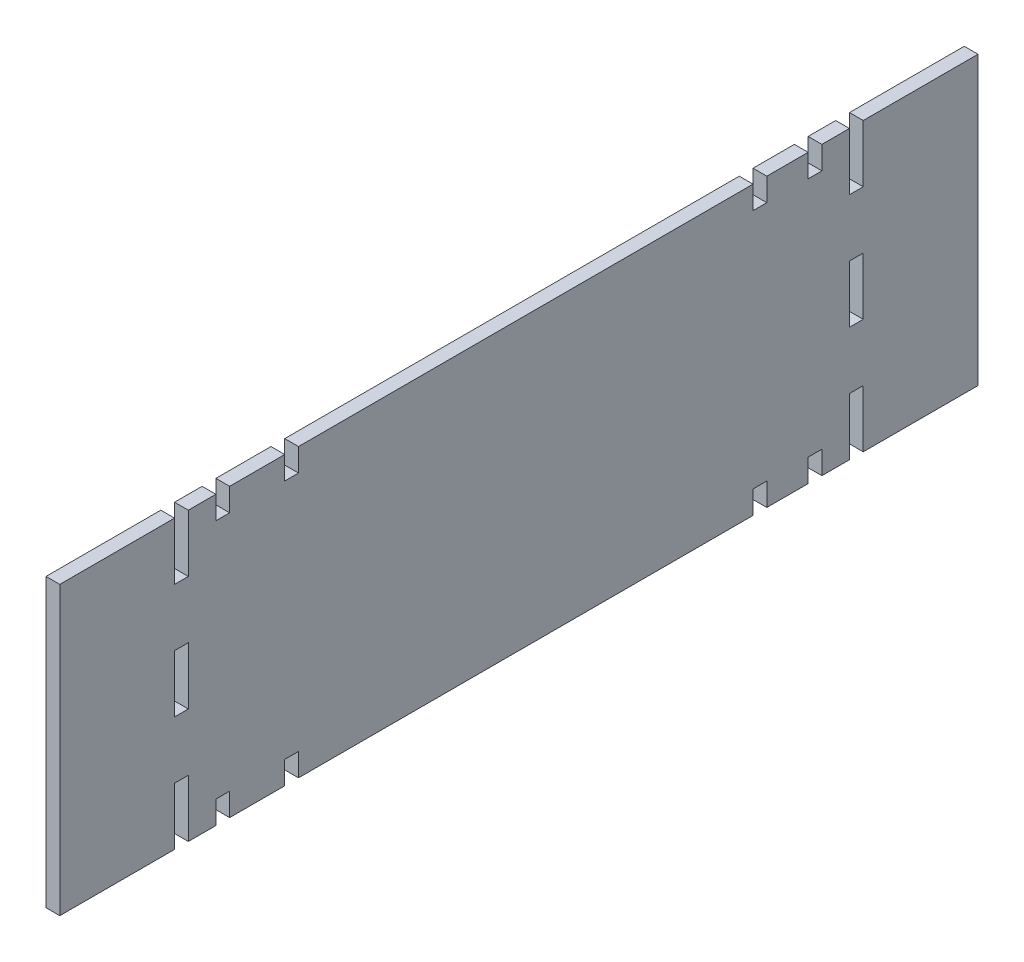
SolidWorks part; units mm, degrees
ref_plane "Front" through (0, 0, 0) normal (0, 0, 1) x (1, 0, 0)
ref_plane "Top" through (0, 0, 0) normal (0, 1, 0) x (1, 0, 0)
ref_plane "Right" through (0, 0, 0) normal (1, 0, 0) x (0, 0, -1)
sketch "Sketch1" plane through (0, 0, 0) normal (1, 0, 0) x (0, 0, -1)
  line L1 (0, 0) -> (-400, 0)
  line L2 (0, 0) -> (0, 125)
  line L3 (0, 125) -> (-400, 125)
  line L4 (-400, 0) -> (-400, 125)
  dimension "D1" = 400
  dimension "D2" = 125
extrude "Boss-Extrude1" add sketch "Sketch1" along normal blind 6
sketch "Sketch3" plane through (6, 0, 0) normal (1, 0, 0) x (0, 0, -1)
  line L0 (-400, 125) -> (-400, 0) construction
  line L1 (-350, 125) -> (-344, 125)
  line L2 (-350, 125) -> (-350, 100)
  line L3 (-350, 100) -> (-344, 100)
  line L4 (-344, 125) -> (-344, 100)
  line L5 (0, 125) -> (-400, 125) construction
  dimension "D1" = 6
  dimension "D2" = 25
  dimension "D3" = 50
extrude "Cut-Extrude1" cut sketch "Sketch3" against normal through all
pattern_linear "LPattern1" count 2 spacing 294 along (0, 0, -1) count 3 spacing 50 along (0, -1, 0) of "Cut-Extrude1"
sketch "Sketch4" plane through (6, 0, 0) normal (1, 0, 0) x (0, 0, -1)
  line L0 (-56, 125) -> (-344, 125) construction
  line L1 (-332, 125) -> (-326, 125)
  line L2 (-332, 125) -> (-332, 115)
  line L3 (-332, 115) -> (-326, 115)
  line L4 (-326, 125) -> (-326, 115)
  line L5 (-344, 100) -> (-344, 125) construction
  dimension "D1" = 6
  dimension "D2" = 12
  dimension "D3" = 10
extrude "Cut-Extrude2" cut sketch "Sketch4" against normal through all
pattern_linear "LPattern2" count 2 spacing 258 along (0, 0, -1) count 2 spacing 115 along (0, -1, 0) of "Cut-Extrude2"
sketch "Sketch5" plane through (6, 0, 0) normal (1, 0, 0) x (0, 0, -1)
  line L0 (-74, 125) -> (-326, 125) construction
  line L1 (-302, 125) -> (-296, 125)
  line L2 (-302, 125) -> (-302, 115)
  line L3 (-302, 115) -> (-296, 115)
  line L4 (-296, 125) -> (-296, 115)
  line L5 (-326, 115) -> (-326, 125) construction
  line L6 (-332, 115) -> (-326, 115) construction
  dimension "D1" = 24
  dimension "D2" = 6
extrude "Cut-Extrude3" cut sketch "Sketch5" against normal through all
pattern_linear "LPattern3" count 2 spacing 115 along (0, -1, 0) count 2 spacing 204 along (0, 0, -1) of "Cut-Extrude3"
